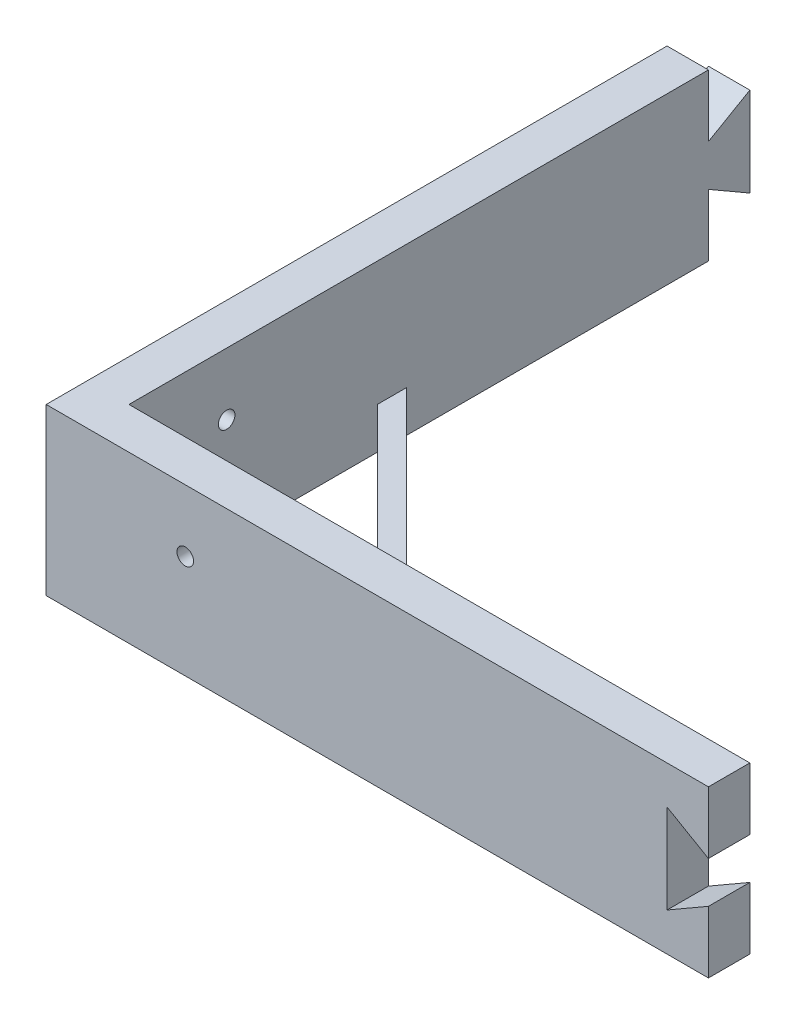
SolidWorks part; units mm, degrees
ref_plane "Front" through (0, 0, 0) normal (0, 0, 1) x (1, 0, 0)
ref_plane "Top" through (0, 0, 0) normal (0, 1, 0) x (1, 0, 0)
ref_plane "Right" through (0, 0, 0) normal (1, 0, 0) x (0, 0, -1)
sketch "Sketch1" plane through (0, 0, 0) normal (0, 0, 1) x (1, 0, 0)
  line L1 (-6.35, 25.4) -> (6.35, 25.4)
  line L2 (-6.35, 25.4) -> (-6.35, -25.4)
  line L3 (-6.35, -25.4) -> (6.35, -25.4)
  line L4 (6.35, 25.4) -> (6.35, -25.4)
  line L5 (-6.35, 25.4) -> (6.35, -25.4) construction
  line L6 (-6.35, -25.4) -> (6.35, 25.4) construction
  point P0 (0, 0)
  dimension "D1" = 50.8
extrude "Boss-Extrude1" add sketch "Sketch1" along normal blind 203.2
sketch "Sketch2" plane through (6.35, 0, 0) normal (1, 0, 0) x (0, 0, -1)
  line L0 (-203.2, -25.4) -> (0, -25.4) construction
  line L1 (-203.2, 25.4) -> (-190.5, 25.4)
  line L2 (-203.2, 25.4) -> (-203.2, -25.4)
  line L3 (-203.2, -25.4) -> (-190.5, -25.4)
  line L4 (-190.5, 25.4) -> (-190.5, -25.4)
  dimension "D1" = 12.7
extrude "Boss-Extrude2" add sketch "Sketch2" along normal blind 190.5
sketch "Sketch5" plane through (0, 0, 0) normal (0, 1, 0) x (1, 0, 0)
  line L0 (6.35, -105.3197) -> (91.5303, -190.5)
  line L1 (6.35, -190.5) -> (6.35, 0) construction
  line L2 (196.85, -190.5) -> (6.35, -190.5) construction
  line L3 (6.35, -114.3) -> (82.55, -190.5)
  line L4 (6.35, -114.3) -> (6.35, -105.3197)
  line L5 (82.55, -190.5) -> (91.5303, -190.5)
  dimension "D1" = 6.35
  dimension "D2" = 45
  dimension "D3" = 76.2
sketch "Sketch6" plane through (0, -25.4, 0) normal (0, -1, 0) x (1, 0, 0)
  line L0 (6.35, 114.3) -> (6.35, 105.3197) construction
  line L1 (82.55, 190.5) -> (91.5303, 190.5) construction
  line L2 (6.35, 114.3) -> (82.55, 190.5) construction
  line L3 (6.35, 105.3197) -> (91.5303, 190.5) construction
  line L4 (6.35, 114.3) -> (6.35, 105.3197)
  line L5 (82.55, 190.5) -> (91.5303, 190.5)
  line L6 (6.35, 114.3) -> (82.55, 190.5)
  line L7 (6.35, 105.3197) -> (91.5303, 190.5)
  dimension "D1" = 76.2
extrude "Boss-Extrude5" add sketch "Sketch6" against normal blind 12.7
sketch "Sketch7" plane through (0, 0, 203.2) normal (0, 0, 1) x (1, 0, 0)
  line L0 (-6.35, -25.4) -> (196.85, -25.4) construction
  line L1 (196.85, 25.4) -> (184.15, 25.4)
  line L2 (196.85, 25.4) -> (196.85, -25.4)
  line L3 (196.85, -25.4) -> (184.15, -25.4)
  line L4 (184.15, 25.4) -> (184.15, -25.4)
  line L5 (184.15, 13.6823) -> (196.85, 6.35)
  line L6 (196.85, 6.35) -> (196.85, 3.6662)
  line L7 (196.85, 25.4) -> (196.85, -25.4) construction
  line L8 (184.15, -3.6662) -> (184.15, -13.6823)
  line L9 (184.15, -13.6823) -> (196.85, -6.35)
  line L11 (184.15, 0) -> (196.85, 0) construction
  line M10 (196.85, -25.4) -> (196.85, 25.4)
  dimension "D1" = 12.7
  dimension "D2" = 60
  dimension "D3" = 60
  dimension "D4" = 19.05
  dimension "D5" = 19.05
extrude "Cut-Extrude2" cut sketch "Sketch7" against normal through all contours L4 L11 L2 L5 M10 | L11 L4 L9 L2
sketch "Sketch8" plane through (6.35, 0, 0) normal (1, 0, 0) x (0, 0, -1)
  line L0 (0, 13.6823) -> (-12.7, 6.35)
  line L1 (0, 25.4) -> (-12.7, 25.4)
  line L2 (0, 25.4) -> (0, -25.4)
  line L3 (0, -25.4) -> (-12.7, -25.4)
  line L4 (-12.7, 25.4) -> (-12.7, -25.4)
  line L5 (-12.7, 6.35) -> (-12.7, -6.35)
  line L6 (-12.7, -6.35) -> (0, -13.6823)
  line L8 (-190.5, -25.4) -> (-114.3, -25.4)
  line L9 (-114.3, -25.4) -> (-114.3, -12.7)
  line L10 (-114.3, -12.7) -> (-105.3197, -12.7)
  line L11 (-105.3197, -12.7) -> (-105.3197, -25.4)
  line L12 (-105.3197, -25.4) -> (0, -25.4)
  line L13 (0, -25.4) -> (0, 25.4)
  line L14 (0, 25.4) -> (-190.5, 25.4)
  line L15 (-190.5, 25.4) -> (-190.5, -25.4)
  line L16 (-190.5, -25.4) -> (-114.3, -25.4)
  line L17 (-114.3, -25.4) -> (-114.3, -12.7)
  line L18 (-114.3, -12.7) -> (-105.3197, -12.7)
  line L19 (-105.3197, -12.7) -> (-105.3197, -25.4)
  line L20 (-105.3197, -25.4) -> (0, -25.4)
  line L21 (0, -25.4) -> (0, 25.4)
  line L22 (0, 25.4) -> (-190.5, 25.4)
  line L23 (-190.5, 25.4) -> (-190.5, -25.4)
  line M19 (-105.3197, -25.4) -> (0, -25.4)
  line M20 (0, -25.4) -> (0, 25.4)
  line M21 (0, 25.4) -> (-190.5, 25.4)
  dimension "D2" = 12.7
  dimension "D3" = 120
  dimension "D4" = 120
  dimension "D5" = 19.05
  dimension "D6" = 19.05
  dimension "D1" = 0
extrude "Cut-Extrude3" cut sketch "Sketch8" against normal through all contours L4 L0 M21 M20 | L6 L4 M19 M20
sketch "Sketch9" plane through (0, 0, 190.5) normal (0, 0, -1) x (-1, 0, 0)
  line L0 (-196.85, 25.4) -> (-6.35, 25.4) construction
  line L1 (-6.35, -25.4) -> (-6.35, 25.4) construction
  circle A0 centre (-36.322, 6.35) radius 2.54
  dimension "D3" = 5.08
  dimension "D1" = 19.05
  dimension "D2" = 29.972
extrude "Cut-Extrude4" cut sketch "Sketch9" against normal through all
sketch "Sketch10" plane through (6.35, 0, 0) normal (1, 0, 0) x (0, 0, -1)
  line L0 (-190.5, 25.4) -> (-12.7, 25.4) construction
  line L1 (-190.5, 6.35) -> (-190.5, 25.4) construction
  circle A0 centre (-160.528, 6.35) radius 2.54
  dimension "D1" = 5.08
  dimension "D2" = 19.05
  dimension "D3" = 29.972
extrude "Cut-Extrude5" cut sketch "Sketch10" against normal through all
